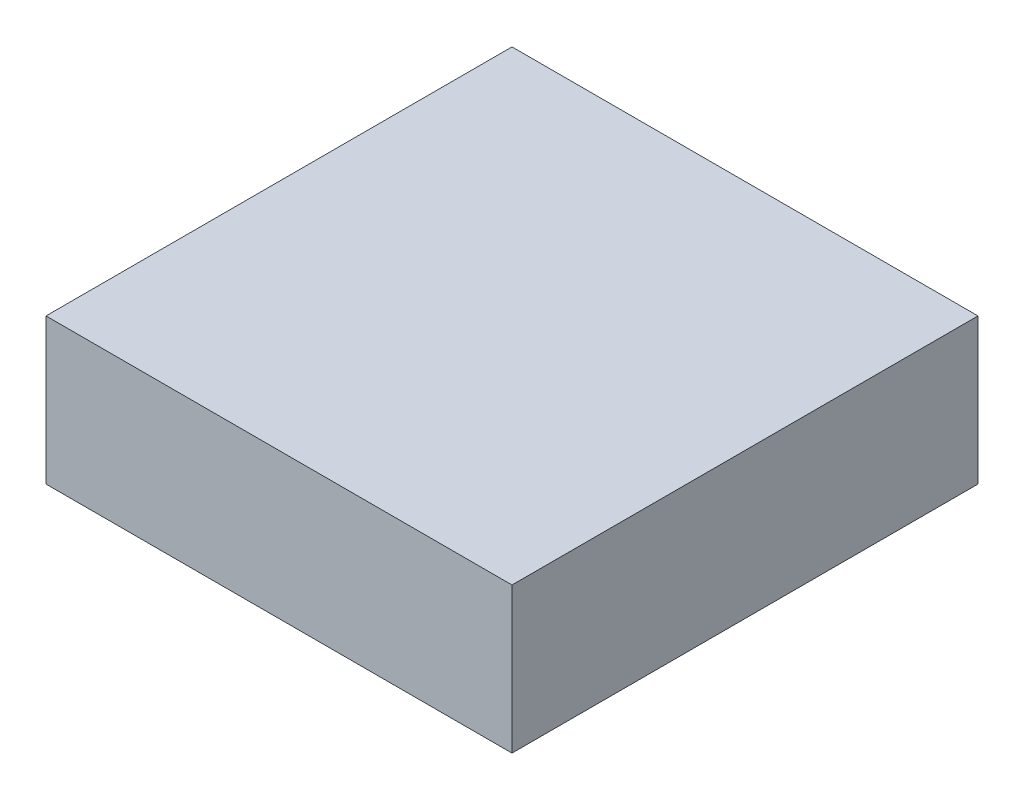
SolidWorks part; units mm, degrees
ref_plane "Front Plane" through (0, 0, 0) normal (0, 0, 1) x (1, 0, 0)
ref_plane "Top Plane" through (0, 0, 0) normal (0, 1, 0) x (1, 0, 0)
ref_plane "Right Plane" through (0, 0, 0) normal (1, 0, 0) x (0, 0, -1)
sketch "Sketch1" plane through (0, 0, 0) normal (0, 1, 0) x (1, 0, 0)
  line L1 (-0.8, -0.8) -> (0.8, -0.8)
  line L2 (-0.8, -0.8) -> (-0.8, 0.8)
  line L3 (-0.8, 0.8) -> (0.8, 0.8)
  line L4 (0.8, -0.8) -> (0.8, 0.8)
  line L5 (-0.8, -0.8) -> (0.8, 0.8) construction
  line L6 (-0.8, 0.8) -> (0.8, -0.8) construction
  point P0 (0, 0)
  dimension "D1" = 1.6
extrude "Boss-Extrude1" add sketch "Sketch1" along normal blind 0.5
